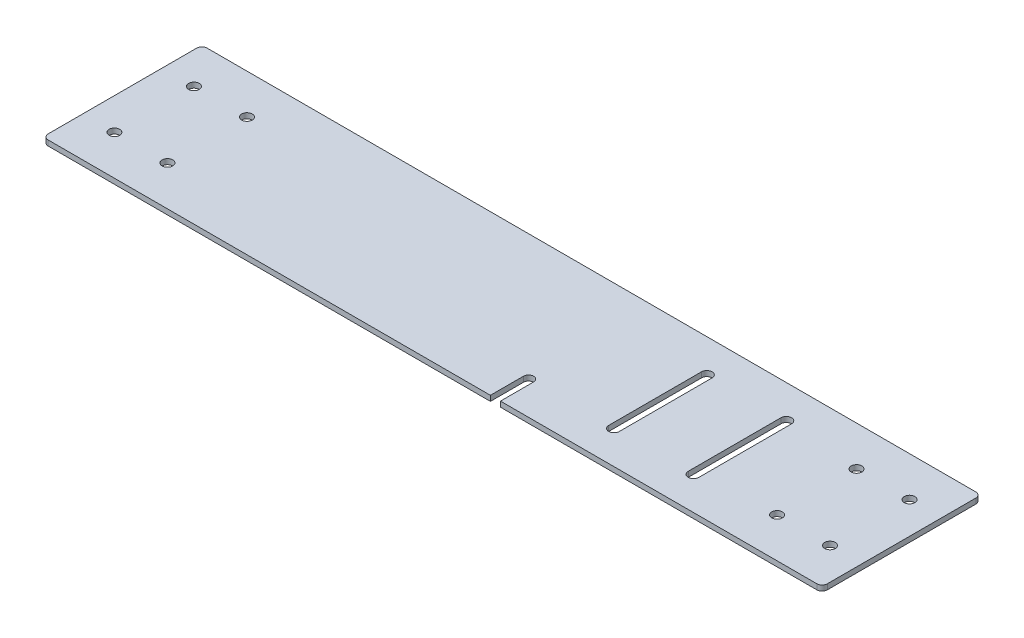
SolidWorks part; units mm, degrees
ref_plane "Front Plane" through (0, 0, 0) normal (0, 0, 1) x (1, 0, 0)
ref_plane "Top Plane" through (0, 0, 0) normal (0, 1, 0) x (1, 0, 0)
ref_plane "Right Plane" through (0, 0, 0) normal (1, 0, 0) x (0, 0, -1)
sketch "Sketch1" plane through (0, 0, 0) normal (0, 1, 0) x (1, 0, 0)
  line L0 (-100, 30) -> (-70, 70)
  line L1 (-147, 30) -> (-100, 30)
  line L2 (-147, 30) -> (-147, -30)
  line L3 (-147, -30) -> (-100, -30)
  line L4 (-100, 30) -> (-100, -30)
  line L5 (100, 30) -> (147, 30)
  line L6 (100, 30) -> (100, -30)
  line L7 (100, -30) -> (147, -30)
  line L8 (147, 30) -> (147, -30)
  line L9 (-70, 70) -> (70, 70)
  line L10 (-70, 70) -> (-70, -70)
  line L11 (-70, -70) -> (70, -70)
  line L12 (70, 70) -> (70, -70)
  line L13 (-100, -30) -> (-70, -70)
  line L14 (100, -30) -> (70, -70)
  line L15 (100, 30) -> (70, 70)
  dimension "D1" = 47
  dimension "D2" = 60
  dimension "D3" = 47
  dimension "D4" = 60
  dimension "D5" = 140
  dimension "D6" = 140
  dimension "D7" = 30
  dimension "D8" = 50
  dimension "D9" = 30
  dimension "D10" = 50
  dimension "D11" = 50
  dimension "D12" = 50
  dimension "D13" = 147
  dimension "D14" = 294
  dimension "D15" = 70
extrude "Boss-Extrude1" add sketch "Sketch1" along normal blind 2 contours L4 L1 L2 L3 | L4 L13 L10 L0 | L12 L9 L10 L11 | L6 L15 L12 L14 | L8 L5 L6 L7
sketch "Sketch2" plane through (0, 2, 0) normal (0, 1, 0) x (1, 0, 0)
  line L0 (-147, 30) -> (-100, 30) construction
  line L1 (-147, -30) -> (-100, -30) construction
  line L3 (-147, 30) -> (-147, -30) construction
  circle A0 centre (-135, 15) radius 2
  circle A1 centre (-115, 15) radius 2
  circle A2 centre (-135, -15) radius 2
  circle A3 centre (-115, -15) radius 2
  dimension "D1" = 4
  dimension "D2" = 4
  dimension "D3" = 4
  dimension "D4" = 4
  dimension "D5" = 20
  dimension "D6" = 20
  dimension "D7" = 30
  dimension "D8" = 30
  dimension "D9" = 12
  dimension "D10" = 12
  dimension "D11" = 15
  dimension "D12" = 15
  dimension "D13" = 15
extrude "Cut-Extrude1" cut sketch "Sketch2" against normal blind 10
mirror "Mirror1" about plane through (0, 0, 0) normal (1, 0, 0) of "Cut-Extrude1"
sketch "Sketch11" plane through (0, 2, 0) normal (0, 1, 0) x (1, 0, 0)
  line L0 (147, 30) -> (147, -30) construction
  line L1 (58, -17.5) -> (58, 17.5)
  line L2 (54, -17.5) -> (54, 17.5)
  line L3 (100, 30) -> (147, 30) construction
  line L4 (100, -30) -> (147, -30) construction
  line L5 (84, -17.5) -> (84, 17.5)
  line L6 (88, -17.5) -> (88, 17.5)
  line L7 (21.85, -17.5) -> (21.85, -47.5)
  line L8 (25.65, -17.5) -> (25.65, -47.5)
  arc A0 (58, 17.5) -> (54, 17.5) centre (56, 17.5) ccw
  arc A1 (88, 17.5) -> (84, 17.5) centre (86, 17.5) ccw
  arc A2 (54, -17.5) -> (58, -17.5) centre (56, -17.5) ccw
  arc A3 (84, -17.5) -> (88, -17.5) centre (86, -17.5) ccw
  arc A4 (25.65, -17.5) -> (21.85, -17.5) centre (23.75, -17.5) ccw
  arc A5 (21.85, -47.5) -> (25.65, -47.5) centre (23.75, -47.5) ccw
  dimension "D1" = 4
  dimension "D2" = 4
  dimension "D3" = 4
  dimension "D4" = 4
  dimension "D14" = 3.8
  dimension "D15" = 3.8
  dimension "D5" = 35
  dimension "D6" = 35
  dimension "D7" = 30
  dimension "D8" = 30
  dimension "D9" = 61
  dimension "D10" = 0
  dimension "D11" = 61
  dimension "D12" = 12.5
  dimension "D13" = 12.5
  dimension "D16" = 30
  dimension "D17" = 30.25
  dimension "D18" = 0
extrude "Cut-Extrude3" cut sketch "Sketch11" against normal blind 10
fillet "Fillet1" radius 2 12 edges at (-147, 1, 30) (-147, 1, -30) (-100, 1, -30) (-70, 1, -70) (70, 1, -70) (100, 1, -30) (147, 1, -30) (147, 1, 30) (100, 1, 30) (70, 1, 70) (-70, 1, 70) (-100, 1, 30)
sketch "Sketch12" plane through (0, 2, 0) normal (0, 1, 0) x (1, 0, 0)
  line L0 (101, 30) -> (145, 30) construction
  line L1 (-111.6962, 72.8115) -> (107.2201, 72.8115)
  line L2 (-111.6962, 72.8115) -> (-111.6962, 30)
  line L3 (-111.6962, 30) -> (107.2201, 30)
  line L4 (107.2201, 72.8115) -> (107.2201, 30)
  line L5 (-145, -30) -> (-101, -30) construction
  line L6 (-111.6962, -30) -> (107.2201, -30)
  line L7 (-111.6962, -30) -> (-111.6962, -71.2635)
  line L8 (-111.6962, -71.2635) -> (107.2201, -71.2635)
  line L9 (107.2201, -30) -> (107.2201, -71.2635)
extrude "Cut-Extrude4" cut sketch "Sketch12" against normal blind 10
